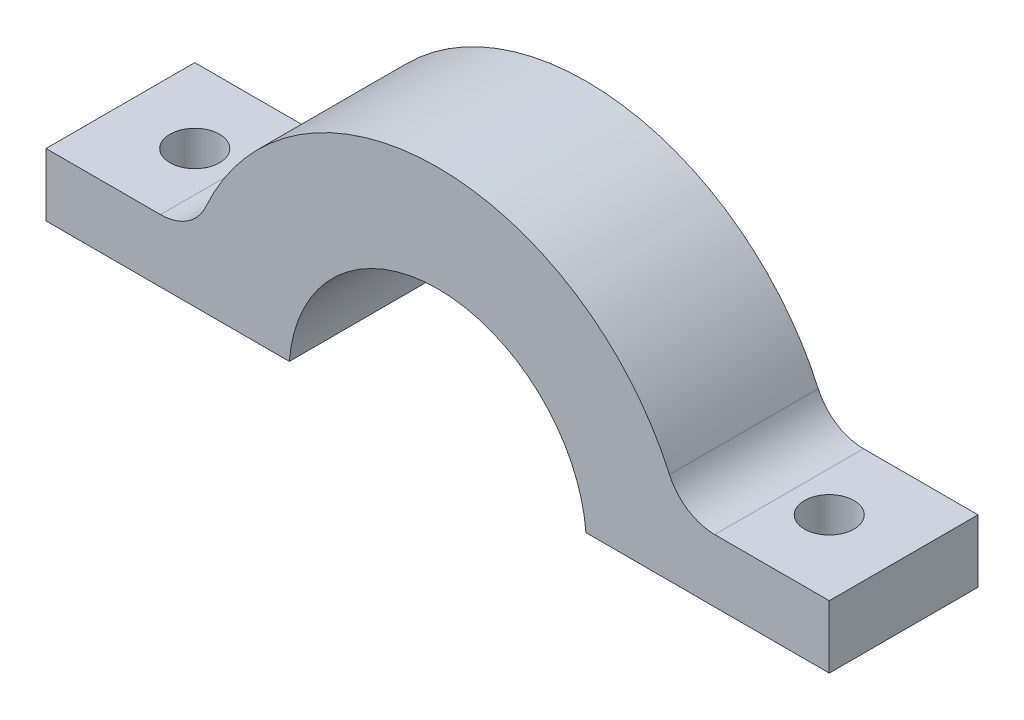
SolidWorks part; units mm, degrees
ref_plane "Front Plane" through (0, 0, 0) normal (0, 0, 1) x (1, 0, 0)
ref_plane "Top Plane" through (0, 0, 0) normal (0, 1, 0) x (1, 0, 0)
ref_plane "Right Plane" through (0, 0, 0) normal (1, 0, 0) x (0, 0, -1)
sketch "Esboço1" plane through (0, 0, 0) normal (0, 0, 1) x (1, 0, 0)
  line L0 (-51.1747, 2.3452) -> (-29.9082, 2.3452)
  line L1 (29.9082, 2.3452) -> (51.1747, 2.3452)
  line L2 (48.9831, 15) -> (78.9831, 15)
  line L3 (-48.9831, 15) -> (-78.9831, 15)
  line L4 (-78.9831, 15) -> (-78.9831, 2.3452)
  line L5 (-78.9831, 2.3452) -> (-51.1747, 2.3452)
  line L6 (51.1747, 2.3452) -> (78.9831, 2.3452)
  line L7 (78.9831, 2.3452) -> (78.9831, 15)
  arc A0 (29.9082, 2.3452) -> (-29.9082, 2.3452) centre (0, 0) ccw
  arc A1 (48.9831, 15) -> (-48.9831, 15) centre (0, 0) ccw
  dimension "D1" = 60
  dimension "D2" = 15
  dimension "D3" = 30
  dimension "D4" = 30
extrude "Ressalto-extrusão1" add sketch "Esboço1" along normal blind 30
sketch "Esboço2" plane through (0, 15, 0) normal (0, 1, 0) x (1, 0, 0)
  line L0 (-48.9831, -30) -> (-78.9831, 0) construction
  line L1 (48.9831, -30) -> (78.9831, 0) construction
  circle A0 centre (-63.9831, -15) radius 5
  circle A1 centre (63.9831, -15) radius 5
  dimension "D1" = 10
  dimension "D2" = 10
extrude "Corte-extrusão1" cut sketch "Esboço2" against normal blind 30
fillet "Filete1" radius 10 2 edges at (-48.9831, 15, 15) (48.9831, 15, 15)
